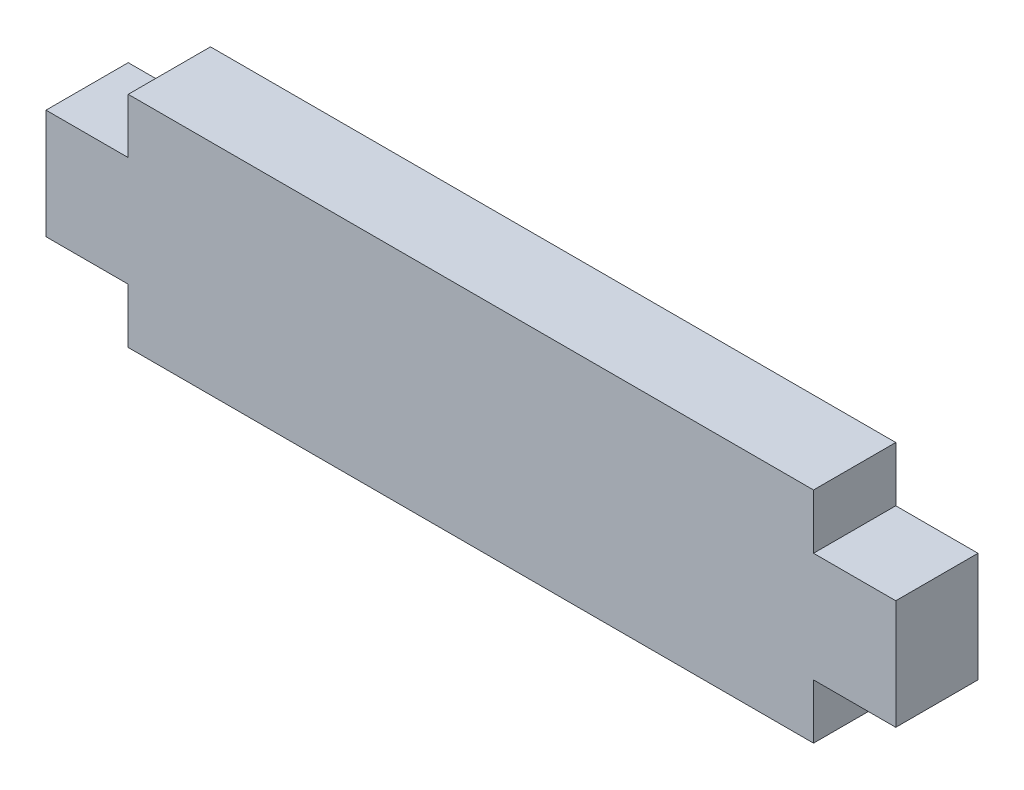
SolidWorks part; units mm, degrees
ref_plane "Plan de face" through (0, 0, 0) normal (0, 0, 1) x (1, 0, 0)
ref_plane "Plan de dessus" through (0, 0, 0) normal (0, 1, 0) x (1, 0, 0)
ref_plane "Plan de droite" through (0, 0, 0) normal (1, 0, 0) x (0, 0, -1)
sketch "Esquisse1" plane through (0, 0, 0) normal (0, 0, 1) x (1, 0, 0)
  line L0 (0, 0) -> (0, 4)
  line L1 (0, 4) -> (-6, 4)
  line L2 (-6, 4) -> (-6, 12)
  line L3 (-6, 12) -> (0, 12)
  line L4 (0, 12) -> (0, 16)
  line L5 (0, 16) -> (50, 16)
  line L6 (50, 16) -> (50, 12)
  line L7 (50, 12) -> (56, 12)
  line L8 (56, 12) -> (56, 4)
  line L9 (56, 4) -> (50, 4)
  line L10 (50, 4) -> (50, 0)
  line L11 (50, 0) -> (0, 0)
  dimension "D1" = 50
  dimension "D2" = 8
  dimension "D3" = 16
  dimension "D4" = 6
extrude "Boss.-Extru.1" add sketch "Esquisse1" along normal blind 6
